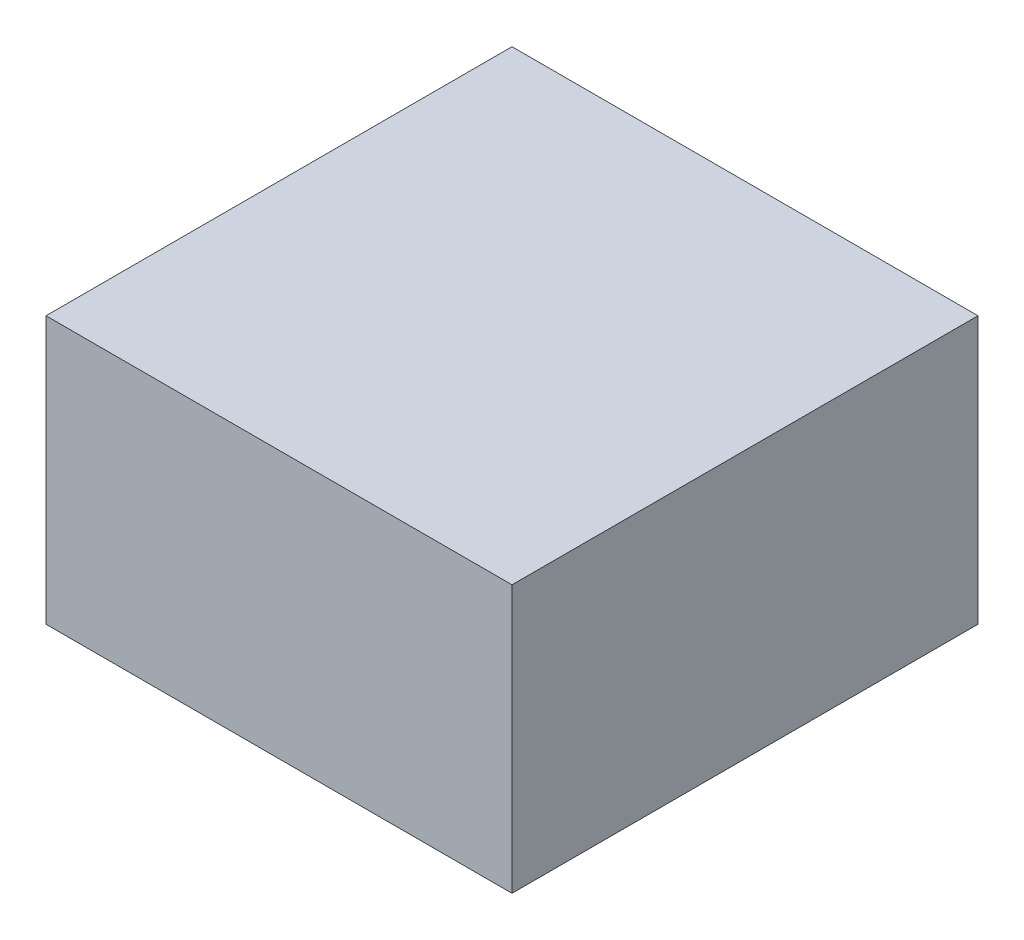
SolidWorks part; units mm, degrees
ref_plane "Front Plane" through (0, 0, 0) normal (0, 0, 1) x (1, 0, 0)
ref_plane "Top Plane" through (0, 0, 0) normal (0, 1, 0) x (1, 0, 0)
ref_plane "Right Plane" through (0, 0, 0) normal (1, 0, 0) x (0, 0, -1)
sketch "Sketch1" plane through (0, 0, 0) normal (0, 0, 1) x (1, 0, 0)
  line L1 (0, 0) -> (150, 0)
  line L2 (0, 0) -> (0, 86)
  line L3 (0, 86) -> (150, 86)
  line L4 (150, 0) -> (150, 86)
  dimension "D1" = 86
  dimension "D2" = 150
extrude "Boss-Extrude1" add sketch "Sketch1" along normal blind 150
